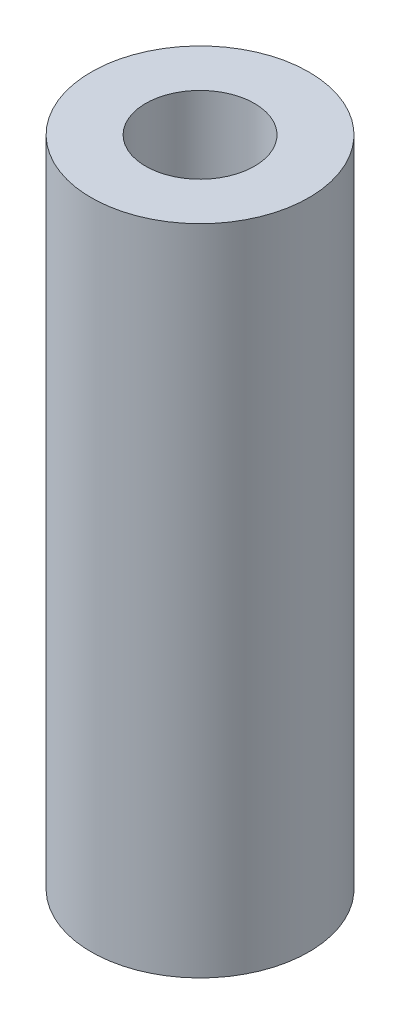
SolidWorks part; units mm, degrees
ref_plane "Front Plane" through (0, 0, 0) normal (0, 0, 1) x (1, 0, 0)
ref_plane "Top Plane" through (0, 0, 0) normal (0, 1, 0) x (1, 0, 0)
ref_plane "Right Plane" through (0, 0, 0) normal (1, 0, 0) x (0, 0, -1)
sketch "Sketch1" plane through (0, 0, 0) normal (0, 1, 0) x (1, 0, 0)
  circle A0 centre (0, 0) radius 6.35
  circle A1 centre (0, 0) radius 3.175
extrude "Boss-Extrude1" add sketch "Sketch1" along normal blind 38.1
